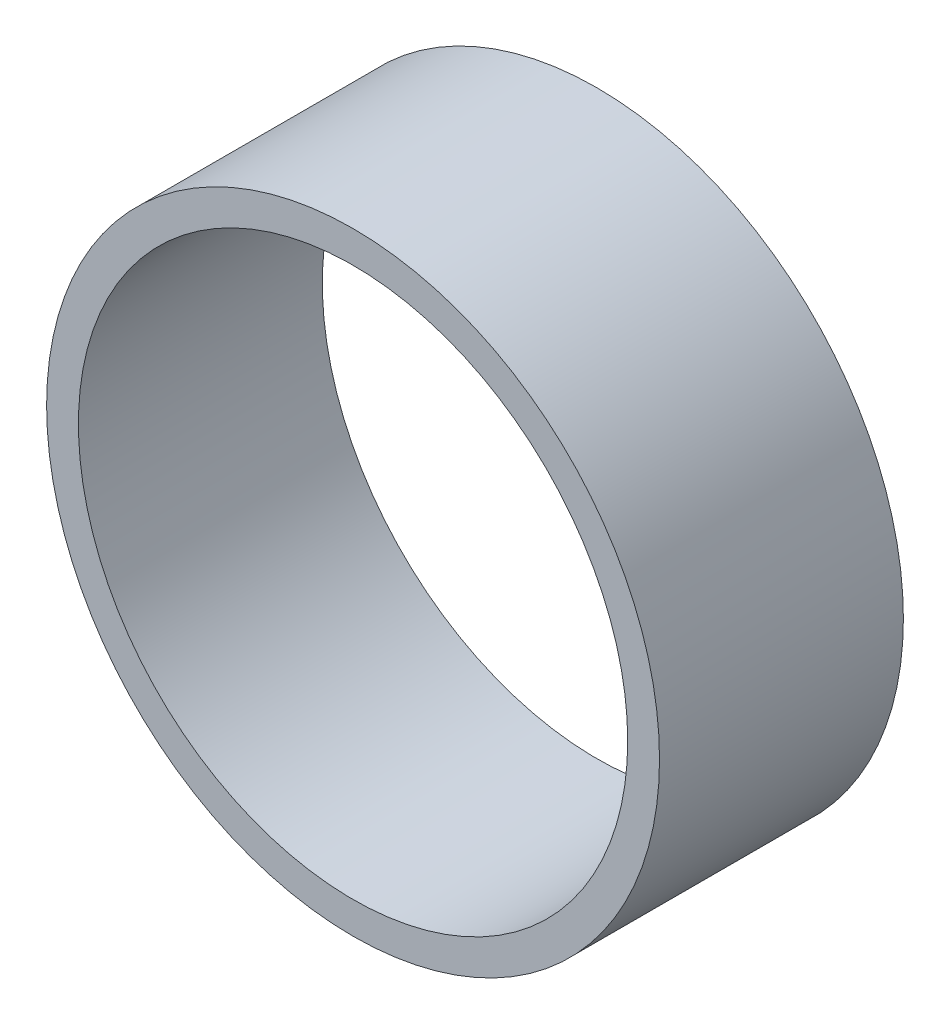
SolidWorks part; units mm, degrees
material "Cast Alloy Steel"
ref_plane "Front Plane" through (0, 0, 0) normal (0, 0, 1) x (1, 0, 0)
ref_plane "Top Plane" through (0, 0, 0) normal (0, 1, 0) x (1, 0, 0)
ref_plane "Right Plane" through (0, 0, 0) normal (1, 0, 0) x (0, 0, -1)
sketch "Sketch1" plane through (0, 0, 0) normal (0, 0, 1) x (1, 0, 0)
  circle A0 centre (0, 0) radius 15.08
  circle A1 centre (0, 0) radius 13.515
extrude "Boss-Extrude1" add sketch "Sketch1" along normal blind 12
